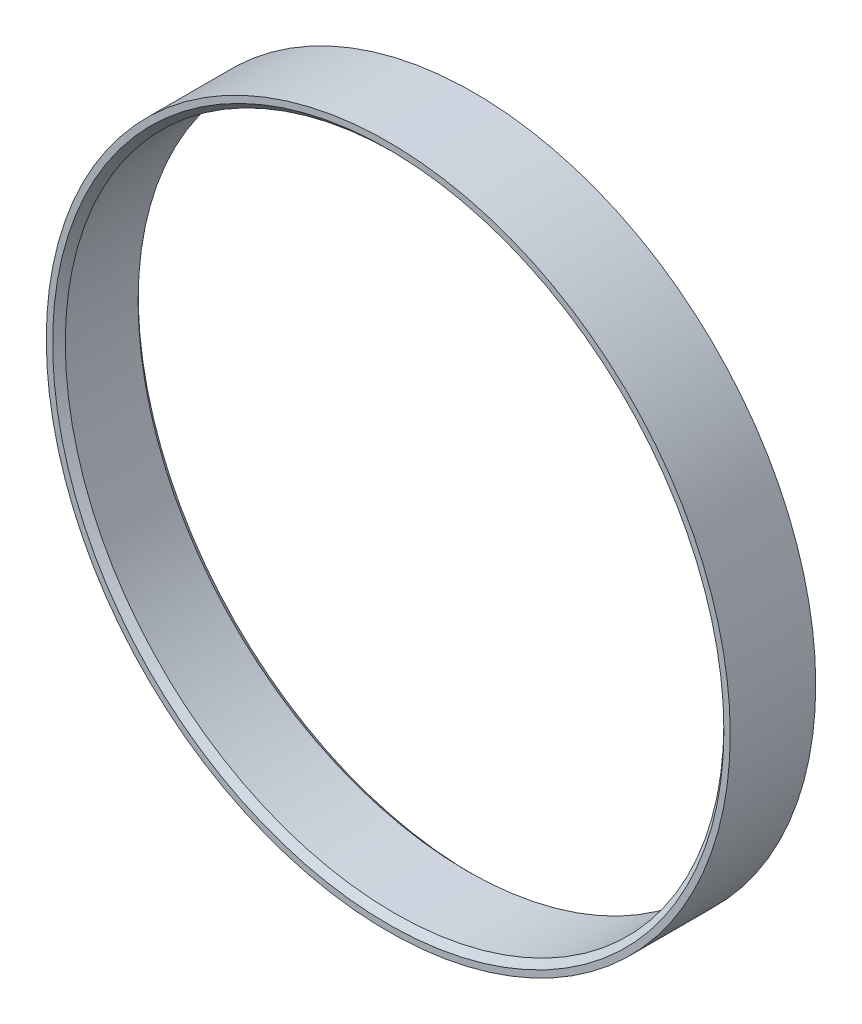
SolidWorks part; units mm, degrees
ref_plane "Płaszczyzna przednia" through (0, 0, 0) normal (0, 0, 1) x (1, 0, 0)
ref_plane "Płaszczyzna górna" through (0, 0, 0) normal (0, 1, 0) x (1, 0, 0)
ref_plane "Płaszczyzna prawa" through (0, 0, 0) normal (1, 0, 0) x (0, 0, -1)
sketch "Szkic1" plane through (0, 0, 0) normal (0, 0, 1) x (1, 0, 0)
  circle A0 centre (0, 0) radius 54
  circle A1 centre (0, 0) radius 52
  dimension "D1" = 108
  dimension "D2" = 104
extrude "Dodanie-wyciągnięcie1" add sketch "Szkic1" along normal blind 13.5
chamfer "Sfazowanie1" distance 1 distance2 1 2 edges at (52, 0, 0) (52, 0, 13.5)
